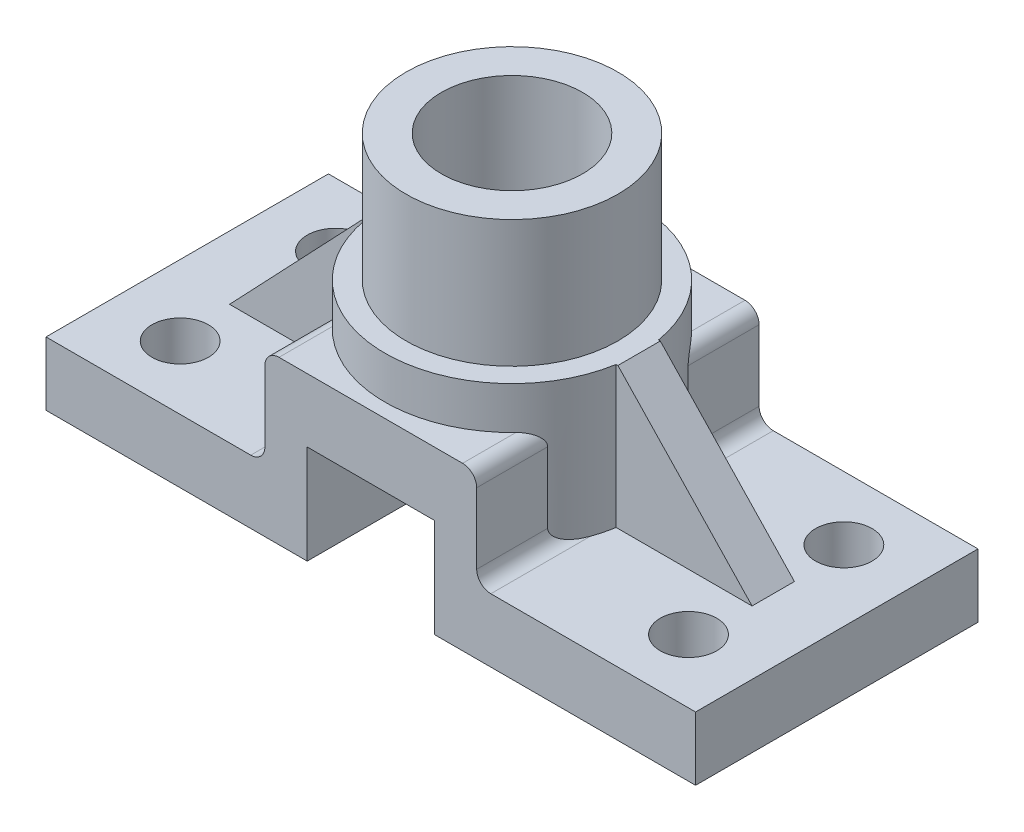
SolidWorks part; units mm, degrees
ref_plane "Front Plane" through (0, 0, 0) normal (0, 0, 1) x (1, 0, 0)
ref_plane "Top Plane" through (0, 0, 0) normal (0, 1, 0) x (1, 0, 0)
ref_plane "Right Plane" through (0, 0, 0) normal (1, 0, 0) x (0, 0, -1)
sketch "Sketch1" plane through (0, 0, 0) normal (0, 0, 1) x (1, 0, 0)
  line L0 (0, 0) -> (9, 0)
  line L1 (9, 0) -> (9, -14)
  line L2 (9, -14) -> (46, -14)
  line L3 (46, -14) -> (46, -5)
  line L4 (46, -5) -> (17, -5)
  line L5 (15, -3) -> (15, 7)
  line L6 (13, 9) -> (0, 9)
  line L7 (0, 0) -> (0, 9)
  arc A0 (15, 7) -> (13, 9) centre (13, 7) ccw
  arc A1 (17, -5) -> (15, -3) centre (17, -3) cw
  point P11 (15, 9)
  point P14 (15, -5)
  dimension "D4" = 2
  dimension "D5" = 2
  dimension "D1" = 9
  dimension "D2" = 14
  dimension "D3" = 9
  dimension "D6" = 37
  dimension "D7" = 6
  dimension "D8" = 9
extrude "Boss-Extrude1" add sketch "Sketch1" against normal blind 40
sketch "Sketch2" plane through (0, -5, 0) normal (0, 1, 0) x (1, 0, 0)
  line L0 (46, 0) -> (17, 0) construction
  line L3 (46, 40) -> (46, 0) construction
  circle A0 centre (36, 9) radius 4
  dimension "D1" = 8
  dimension "D2" = 9
  dimension "D3" = 10
extrude "Cut-Extrude1" cut sketch "Sketch2" against normal blind 40
sketch "Sketch3" plane through (0, -5, 0) normal (0, 1, 0) x (1, 0, 0)
  line L0 (46, 40) -> (46, 0) construction
  line L2 (46, 40) -> (17, 40) construction
  circle A0 centre (36, 31) radius 4
  dimension "D1" = 10
  dimension "D2" = 9
  dimension "D3" = 8
extrude "Cut-Extrude2" cut sketch "Sketch3" against normal blind 40
ref_plane "Plane1" through (0, 15, 0) normal (0, 1, 0) x (1, 0, 0)
sketch "Sketch4" plane through (0, 15, 0) normal (0, 1, 0) x (1, 0, 0)
  line L0 (0, 30) -> (0, 35)
  line L2 (0, 5) -> (0, 10)
  line L3 (13, 40) -> (0, 40) construction
  line L6 (13, 40) -> (13, 0) construction
  arc A1 (0, 5) -> (0, 35) centre (0, 20) ccw
  arc A2 (0, 10) -> (0, 30) centre (0, 20) ccw
  dimension "D1" = 15
  dimension "D2" = 10
  dimension "D4" = 20
  dimension "D5" = 13
  dimension "D6" = 5
  dimension "D3" = 5
extrude "Boss-Extrude4" add sketch "Sketch4" along normal blind 18 separate body
sketch "Sketch7" plane through (0, 15, 0) normal (0, 1, 0) x (1, 0, 0)
  line L0 (0, 2) -> (0, 20)
  line L1 (0, 20) -> (0, 38)
  line L2 (15, 40) -> (15, 0) construction
  line L3 (13, 40) -> (0, 40) construction
  arc A0 (0, 2) -> (0, 38) centre (0, 20) ccw
  dimension "D1" = 18
  dimension "D2" = 15
  dimension "D3" = 20
extrude "Boss-Extrude5" add sketch "Sketch7" against normal up to body separate body
sketch "Sketch13" plane through (0, -5, 0) normal (0, 1, 0) x (1, 0, 0)
  line L0 (46, 20) -> (18, 20)
  line L1 (46, 40) -> (46, 0) construction
  line L2 (18, 20) -> (46, 20)
  arc A0 (17, 14.0839) -> (17, 25.9161) centre (0, 20) ccw construction
ref_plane "Plane6" through (0, 0, -20) normal (0, 0, -1) x (-1, 0, 0)
sketch "Sketch14" plane through (0, 0, -20) normal (0, 0, -1) x (-1, 0, 0)
  line L0 (-46, -5) -> (-18, -5) construction
  line L1 (-37, -5) -> (-18, 15)
  dimension "D1" = 27.5862
  dimension "D2" = 46.469
rib "Rib7" sketch "Sketch14" sketch "Sketch14" thickness 6 extrusion direction parallel to sketch draft on no parameters "D1"=6
sketch "Sketch16" plane through (0, 15, 0) normal (0, 1, 0) x (1, 0, 0)
  circle A0 centre (0, 20) radius 18
  circle A1 centre (0, 20) radius 15
extrude "Cut-Extrude7" cut sketch "Sketch17" against normal blind 30
sketch "Sketch17" plane through (46, 0, 0) normal (1, 0, 0) x (0, 0, -1)
  line L0 (0, -14) -> (0, -5) construction
  line L1 (40, -14) -> (0, -14) construction
  line L3 (20, 15) -> (35.0067, 15)
  line L5 (20, 24.7922) -> (35.0067, 24.7922)
  line L6 (35.0067, 15) -> (35.0067, 24.7922)
  line L7 (20, 15) -> (5.1674, 15)
  line L9 (20, 24.7922) -> (5.1674, 24.7922)
  line L10 (5.1674, 15) -> (5.1674, 24.7922)
  dimension "D1" = 5.1674
  dimension "D2" = 20
  dimension "D3" = 35.0067
  dimension "D4" = 29
  dimension "D5" = 38.7922
sketch "Sketch18" plane through (0, 15, 0) normal (0, 1, 0) x (1, 0, 0)
  circle A0 centre (0, 20) radius 18
  circle A1 centre (0, 20) radius 15
  dimension "D1" = 30
  dimension "D2" = 36
extrude "Cut-Extrude8" cut sketch "Sketch18" along normal blind 30
mirror "Mirror13" about plane through (0, 0, -40) normal (-1, 0, 0) of bodies 115
extrude "Cut-Extrude5" cut sketch "Sketch16" along normal blind 18
